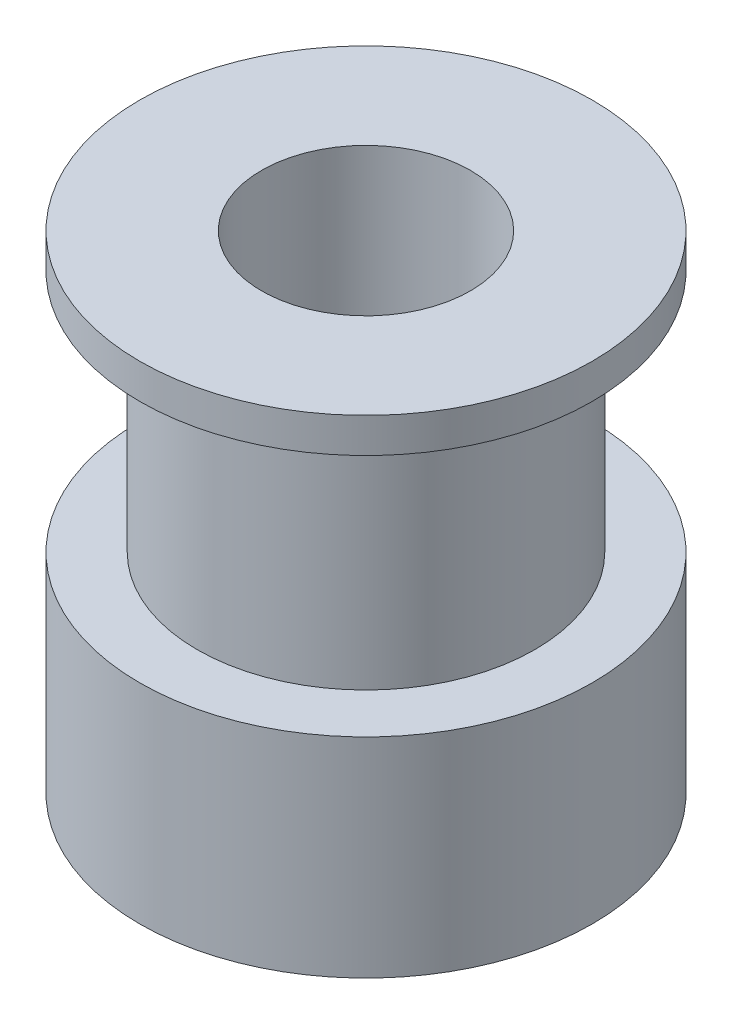
SolidWorks part; units mm, degrees
ref_plane "Front Plane" through (0, 0, 0) normal (0, 0, 1) x (1, 0, 0)
ref_plane "Top Plane" through (0, 0, 0) normal (0, 1, 0) x (1, 0, 0)
ref_plane "Right Plane" through (0, 0, 0) normal (1, 0, 0) x (0, 0, -1)
sketch "Sketch1" plane through (0, 0, 0) normal (0, 0, 1) x (1, 0, 0)
  line L0 (6.5, 0) -> (6.5, 6)
  line L1 (6.5, 6) -> (4.85, 6)
  line L2 (4.85, 6) -> (4.85, 13)
  line L3 (4.85, 13) -> (6.5, 13)
  line L4 (6.5, 13) -> (6.5, 14)
  line L5 (6.5, 14) -> (3, 14)
  line L6 (0, 0) -> (0, 14) construction
  line L7 (6.5, 0) -> (3, 0)
  line L8 (3, 14) -> (3, 0)
  dimension "D1" = 14
  dimension "D2" = 6
  dimension "D3" = 1
  dimension "D4" = 3
  dimension "D5" = 6.5
  dimension "D6" = 4.85
revolve "Revolve1" add sketch "Sketch1" angle 360 about L6
